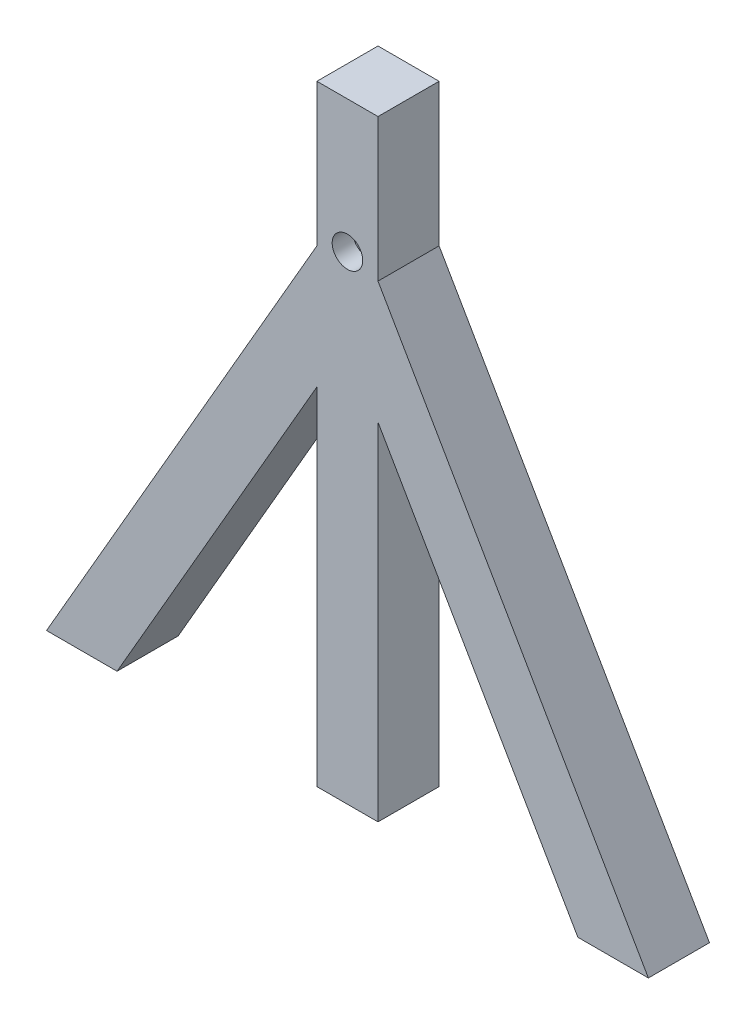
SolidWorks part; units mm, degrees
material "Mahogany"
ref_plane "Front Plane" through (0, 0, 0) normal (0, 0, 1) x (1, 0, 0)
ref_plane "Top Plane" through (0, 0, 0) normal (0, 1, 0) x (1, 0, 0)
ref_plane "Right Plane" through (0, 0, 0) normal (1, 0, 0) x (0, 0, -1)
sketch "Sketch1" plane through (0, 0, 0) normal (0, 0, 1) x (1, 0, 0)
  line L0 (-15, 20) -> (-113.1495, -150)
  line L1 (-15, -150) -> (15, -150)
  line L2 (-15, -150) -> (-15, 20)
  line L3 (-15, 150) -> (15, 150)
  line L4 (15, -150) -> (15, 20)
  line L5 (-15, -150) -> (15, 150) construction
  line L6 (-15, 150) -> (15, -150) construction
  line L7 (-113.1495, -150) -> (-147.7906, -150)
  line L8 (-147.7906, -150) -> (-15, 80)
  line L9 (-15, 80) -> (-15, 150)
  line L10 (0, -150) -> (0, -272.9743) construction
  line L11 (15, 20) -> (113.1495, -150)
  line L12 (113.1495, -150) -> (147.7906, -150)
  line L13 (147.7906, -150) -> (15, 80)
  line L14 (15, 80) -> (15, 150)
  point P0 (0, 0)
  dimension "D1" = 300
  dimension "D2" = 30
  dimension "D3" = 30
  dimension "D4" = 170
  dimension "D5" = 30
extrude "Boss-Extrude1" add sketch "Sketch1" along normal blind 30
sketch "Sketch2" plane through (0, 0, 30) normal (0, 0, 1) x (1, 0, 0)
  line L0 (15, 150) -> (-15, 150) construction
  circle A0 centre (0, 85) radius 7.5
  dimension "D2" = 15
  dimension "D1" = 65
extrude "Cut-Extrude1" cut sketch "Sketch2" against normal blind 10
